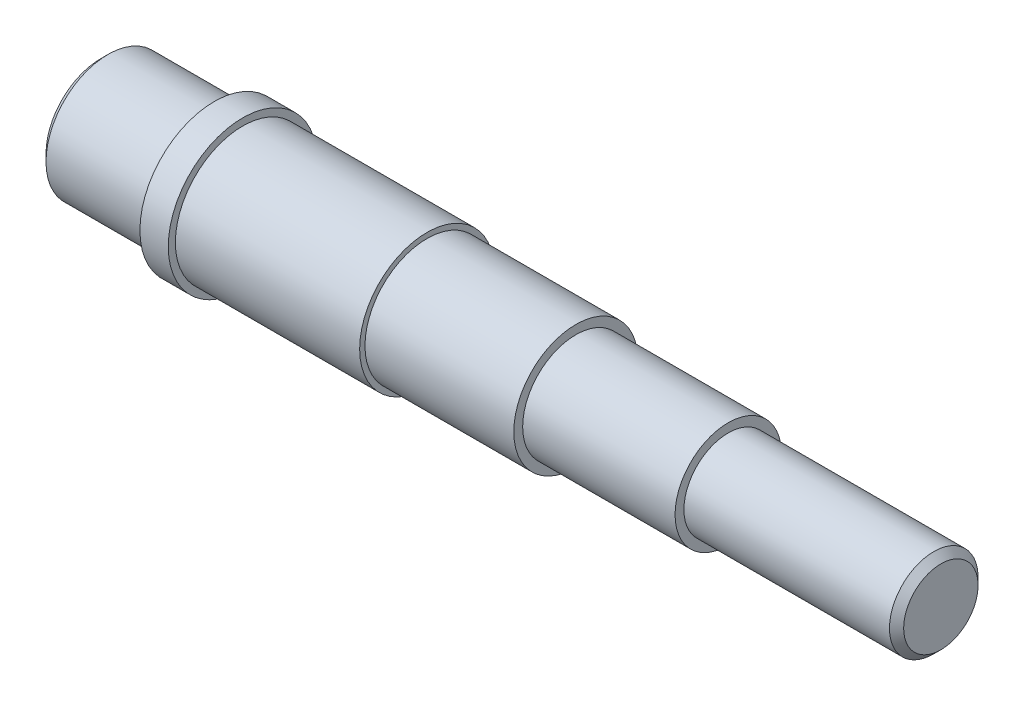
SolidWorks part; units mm, degrees
ref_plane "前视基准面" through (0, 0, 0) normal (0, 0, 1) x (1, 0, 0)
ref_plane "上视基准面" through (0, 0, 0) normal (0, 1, 0) x (1, 0, 0)
ref_plane "右视基准面" through (0, 0, 0) normal (1, 0, 0) x (0, 0, -1)
sketch "草图1" plane through (0, 0, 0) normal (0, 1, 0) x (1, 0, 0)
  line L0 (-134.0375, 0) -> (136.5866, 0) construction
  line L1 (-128.1233, 0) -> (-128.1233, 15.5)
  line L2 (-126.1233, 17.5) -> (-96.1233, 17.5)
  line L3 (-96.1233, 17.5) -> (-96.1233, 21)
  line L4 (-96.1233, 21) -> (-88.1233, 21)
  line L5 (-88.1233, 21) -> (-88.1233, 19)
  line L6 (-88.1233, 19) -> (-36.1233, 19)
  line L7 (-36.1233, 19) -> (-36.1233, 17.5)
  line L8 (-36.1233, 17.5) -> (5.8767, 17.5)
  line L9 (5.8767, 17.5) -> (5.8767, 15)
  line L10 (5.8767, 15) -> (48.8767, 15)
  line L11 (48.8767, 15) -> (48.8767, 12.5)
  line L12 (48.8767, 12.5) -> (106.8767, 12.5)
  line L13 (108.8767, 10.5) -> (108.8767, 0)
  line L14 (-128.1233, 15.5) -> (-126.1233, 17.5)
  line L15 (106.8767, 12.5) -> (108.8767, 10.5)
  line L16 (-128.1233, 0) -> (108.8767, 0)
  point P4 (-128.1233, 17.5)
  point P16 (108.8767, 12.5)
  dimension "D1" = 237
  dimension "D2" = 32
  dimension "D3" = 8
  dimension "D4" = 52
  dimension "D5" = 42
  dimension "D6" = 60
  dimension "D7" = 17.5
  dimension "D8" = 21
  dimension "D9" = 19
  dimension "D10" = 17.5
  dimension "D11" = 15
  dimension "D12" = 12.5
revolve "旋转1" add sketch "草图1" angle 360 about L16
ref_plane "基准面1" through (0, 0, -12.5) normal (0, 0, -1) x (-1, 0, 0)
sketch "草图2" plane through (0, 0, -12.5) normal (0, 0, -1) x (-1, 0, 0)
  line L3 (-101.8767, 4) -> (-53.8767, 4)
  line L7 (-101.8767, -4) -> (-53.8767, -4)
  arc A0 (-101.8767, 4) -> (-101.8767, -4) centre (-101.8767, 0) ccw
  arc A1 (-53.8767, -4) -> (-53.8767, 4) centre (-53.8767, 0) ccw
extrude "切除-拉伸1" cut sketch "草图2" against normal blind 4
ref_plane "基准面2" through (0, 0, -19) normal (0, 0, -1) x (-1, 0, 0)
sketch "草图3" plane through (0, 0, -19) normal (0, 0, -1) x (-1, 0, 0)
  line L3 (44.1233, 5) -> (79.1233, 5)
  line L7 (44.1233, -5) -> (79.1233, -5)
  arc A0 (44.1233, 5) -> (44.1233, -5) centre (44.1233, 0) ccw
  arc A1 (79.1233, -5) -> (79.1233, 5) centre (79.1233, 0) ccw
extrude "切除-拉伸2" cut sketch "草图3" against normal blind 5
